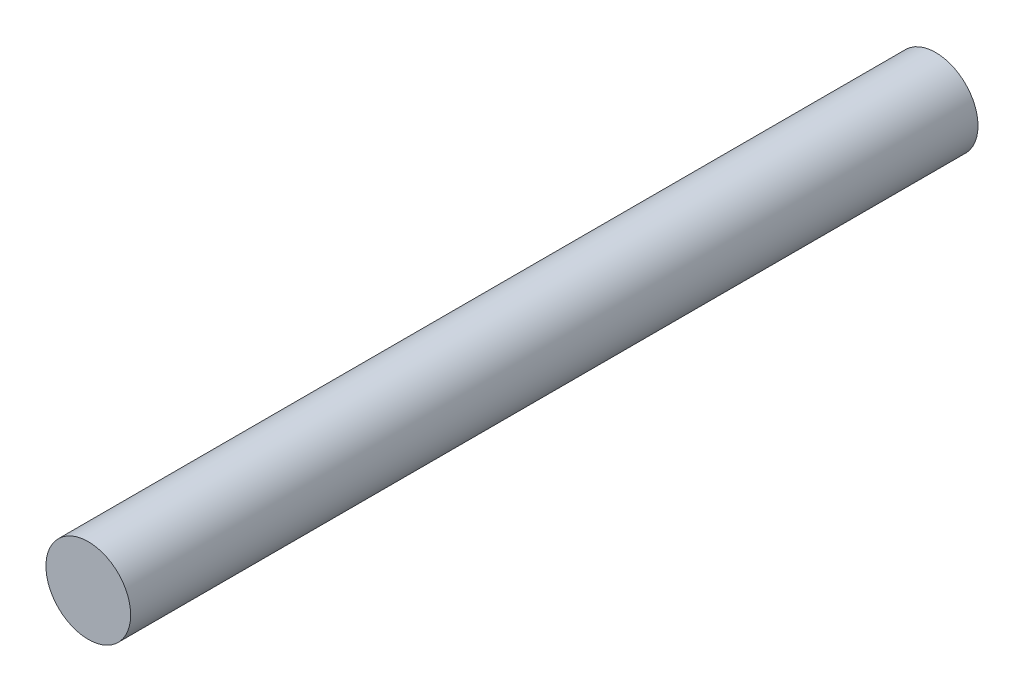
SolidWorks part; units mm, degrees
ref_plane "Front Plane" through (0, 0, 0) normal (0, 0, 1) x (1, 0, 0)
ref_plane "Top Plane" through (0, 0, 0) normal (0, 1, 0) x (1, 0, 0)
ref_plane "Right Plane" through (0, 0, 0) normal (1, 0, 0) x (0, 0, -1)
sketch "Sketch1" plane through (0, 0, 0) normal (0, 0, 1) x (1, 0, 0)
  circle A0 centre (0, 0) radius 5
extrude "Boss-Extrude1" add sketch "Sketch1" along normal mid plane 100
